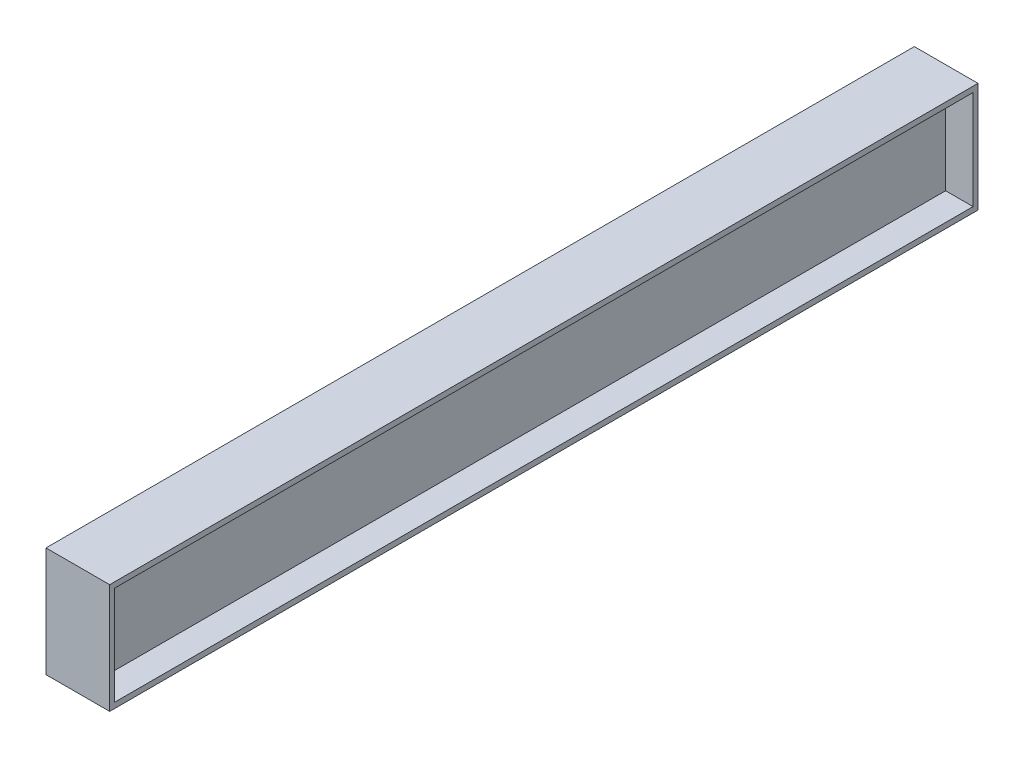
SolidWorks part; units mm, degrees
ref_plane "Front Plane" through (0, 0, 0) normal (0, 0, 1) x (1, 0, 0)
ref_plane "Top Plane" through (0, 0, 0) normal (0, 1, 0) x (1, 0, 0)
ref_plane "Right Plane" through (0, 0, 0) normal (1, 0, 0) x (0, 0, -1)
sketch "Sketch1" plane through (0, 0, 0) normal (0, 0, 1) x (1, 0, 0)
  line L0 (-13.3333, -4.4539) -> (-13.3333, 145.5461)
  line L1 (-13.3333, 145.5461) -> (-96.6663, 145.5461)
  line L2 (-96.6663, 145.5461) -> (-96.6663, 162.2128)
  line L3 (-96.6663, 162.2128) -> (-13.3333, 162.2128)
  line L4 (-13.3333, 162.2128) -> (0, 162.2128)
  line L5 (-13.3333, -4.4539) -> (-13.3333, -154.4539)
  line L6 (-13.3333, -154.4539) -> (-96.6667, -154.4539)
  line L7 (0, 162.2128) -> (96.6667, 162.2128)
  line L8 (96.6667, 162.2128) -> (96.6667, 145.5461)
  line L9 (96.6667, 145.5461) -> (13.3333, 145.5461)
  line L14 (-96.6667, -171.1205) -> (-96.6667, -154.4539)
  line L15 (-96.6667, -171.1205) -> (96.6667, -171.1205)
  line L16 (96.6667, -171.1205) -> (96.6667, -154.4539)
  line L17 (96.6667, -154.4539) -> (13.3333, -154.4539)
  line L18 (13.3333, -154.4539) -> (13.3333, 145.5461)
  dimension "D1" = 16.6667
  dimension "D2" = 150
  dimension "D3" = 13.3333
  dimension "D4" = 0
  dimension "D5" = 83.333
  dimension "D6" = 0
  dimension "D7" = 83.3333
  dimension "D8" = 150
  dimension "D9" = 26.6667
  dimension "D10" = 83.3333
  dimension "D11" = 16.6667
extrude "Boss-Extrude1" add sketch "Sketch1" along normal blind 2636.78
sketch "Sketch2" plane through (0, 0, 0) normal (0, 0, -1) x (-1, 0, 0)
  line L1 (-96.6667, 145.5461) -> (96.6667, 145.5461)
  line L2 (-96.6667, 145.5461) -> (-96.6667, -154.4539)
  line L3 (-96.6667, -154.4539) -> (96.6667, -154.4539)
  line L4 (96.6667, 145.5461) -> (96.6667, -154.4539)
extrude "Boss-Extrude2" add sketch "Sketch2" against normal blind 15
sketch "Sketch3" plane through (0, 0, 2636.78) normal (0, 0, 1) x (1, 0, 0)
  line L1 (-96.6663, 145.5461) -> (96.6667, 145.5461)
  line L2 (-96.6663, 145.5461) -> (-96.6663, -154.4539)
  line L3 (-96.6663, -154.4539) -> (96.6667, -154.4539)
  line L4 (96.6667, 145.5461) -> (96.6667, -154.4539)
extrude "Boss-Extrude4" add sketch "Sketch3" against normal blind 15
